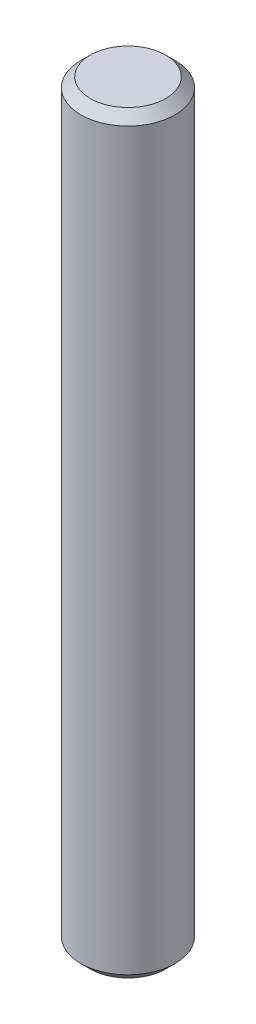
SolidWorks part; units mm, degrees
ref_plane "Front Plane" through (0, 0, 0) normal (0, 0, 1) x (1, 0, 0)
ref_plane "Top Plane" through (0, 0, 0) normal (0, 1, 0) x (1, 0, 0)
ref_plane "Right Plane" through (0, 0, 0) normal (1, 0, 0) x (0, 0, -1)
sketch "Sketch1" plane through (0, 0, 0) normal (0, 1, 0) x (1, 0, 0)
  circle A0 centre (0, 0) radius 2.5
extrude "Boss-Extrude1" add sketch "Sketch1" along normal blind 40
chamfer "Chamfer1" distance 0.5 angle 45 2 edges at (0, 0, 2.5) (0, 40, 2.5)
